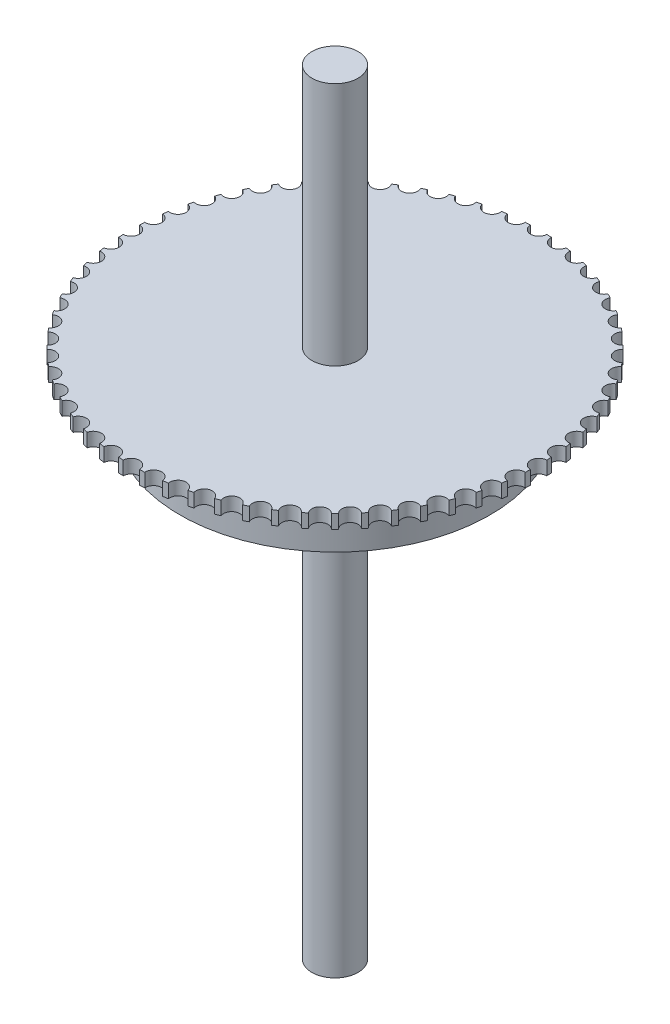
SolidWorks part; units mm, degrees
ref_plane "Alzado" through (0, 0, 0) normal (0, 0, 1) x (1, 0, 0)
ref_plane "Planta" through (0, 0, 0) normal (0, 1, 0) x (1, 0, 0)
ref_plane "Vista lateral" through (0, 0, 0) normal (1, 0, 0) x (0, 0, -1)
sketch "Sketch1" plane through (0, 0, 0) normal (0, 0, 1) x (1, 0, 0)
  line L0 (0, 31.7464) -> (-8.5, 31.7464)
  line L1 (0, -55) -> (0, 55) construction
  line L2 (-8.5, 31.7464) -> (-8.5, -58.2536)
  line L3 (-8.5, -58.2536) -> (-75, -58.2536)
  line L4 (-75, -58.2536) -> (-75, -63.2536)
  line L5 (-75, -63.2536) -> (-57, -63.2536)
  line L6 (-57, -63.2536) -> (-57, -83.2536)
  line L7 (-57, -83.2536) -> (-8.5, -83.2536)
  line L8 (-8.5, -83.2536) -> (-8.5, -253.2536)
  line L9 (-8.5, -253.2536) -> (0, -253.2536)
  line L10 (0, -253.2536) -> (0, 31.7464)
  dimension "D1" = 8.5
  dimension "D2" = 90
  dimension "D3" = 75
  dimension "D4" = 5
  dimension "D5" = 20
  dimension "D6" = 57
  dimension "D7" = 170
  dimension "8.5" = 8.5
revolve "Revolve1" add sketch "Sketch1" angle 360 about L10
hole_wizard "Ø6.0mm Dowel Hole1" positions "Sketch3" profile "Sketch4" hole size "Ø6.0" standard "ISO" end condition through all
sketch "Sketch3" plane through (0, -58.2536, 0) normal (0, 1, 0) x (1, 0, 0)
  line L0 (0, -55) -> (0, 55) construction
  circle A0 centre (0, 0) radius 75 construction
  point P0 (0, 75)
sketch "Sketch4" plane through (0, -58.2536, -75) normal (1, 0, 0) x (0, 0, 1)
  line L0 (0, 0) -> (0, 195)
  line L1 (0, 195) -> (3, 195)
  line L2 (3, 195) -> (3, 0)
  line L5 (3, 0) -> (0, 0)
  line L11 (0, -6.35) -> (0, 107.95) construction
  dimension "Thru Hole Dia." = 6
  dimension "Thru Hole Depth" = 195
pattern_circular "CirPattern1" count 60 every 6 about axis through (0, 0, 0) along (0, 1, 0) of "Ø6.0mm Dowel Hole1"
